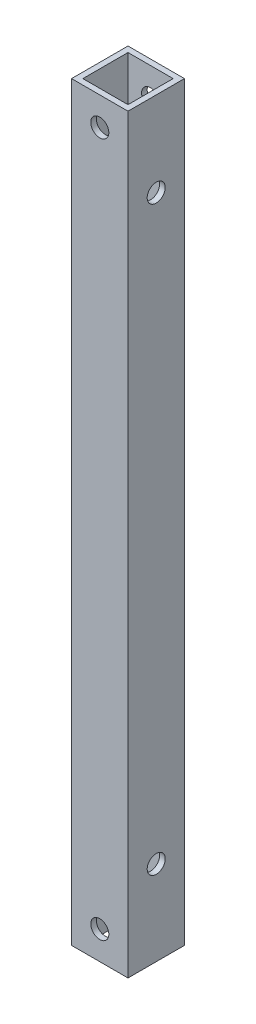
SolidWorks part; units mm, degrees
ref_plane "正面" through (0, 0, 0) normal (0, 0, 1) x (1, 0, 0)
ref_plane "平面" through (0, 0, 0) normal (0, 1, 0) x (1, 0, 0)
ref_plane "右側面" through (0, 0, 0) normal (1, 0, 0) x (0, 0, -1)
sketch "ｽｹｯﾁ1" plane through (0, 0, 0) normal (0, 0, 1) x (1, 0, 0)
  line L0 (460, 0) -> (0, 0) construction
  line L1 (17.4998, 0) -> (27.4998, 0)
  line L2 (17.4998, 0) -> (17.4998, -133)
  line L3 (17.4998, -133) -> (27.4998, -133)
  line L4 (27.4998, 0) -> (27.4998, -133)
  line L5 (459.9998, -133) -> (-0.0002, -133) construction
  line L6 (-0.0002, -133) -> (-0.0002, -123) construction
  line L7 (22.4998, 0) -> (22.4998, -133) construction
  circle A0 centre (22.4998, -5) radius 1.6
  circle A1 centre (22.4998, -128) radius 1.6
  dimension "D3" = 3.2
  dimension "D4" = 5
  dimension "D5" = 5
  dimension "D1" = 10
  dimension "D2" = 17.5
extrude "ﾎﾞｽ - 押し出し1" add sketch "ｽｹｯﾁ1" along normal blind 10
sketch "ｽｹｯﾁ2" plane through (27.4998, 0, 0) normal (1, 0, 0) x (0, 0, -1)
  line L0 (-5, 0) -> (-5, -133) construction
  line L1 (-10, 0) -> (0, 0) construction
  line L2 (-10, -133) -> (0, -133) construction
  circle A0 centre (-5, -118) radius 1.6
  circle A1 centre (-5, -15) radius 1.6
  dimension "D1" = 3.2
  dimension "D2" = 15
  dimension "D3" = 15
extrude "ｶｯﾄ - 押し出し1" cut sketch "ｽｹｯﾁ2" against normal blind 15
sketch "ｽｹｯﾁ3" plane through (0, -133, 0) normal (0, -1, 0) x (1, 0, 0)
  line L8 (18.4998, 1) -> (26.4998, 1)
  line L9 (26.4998, 1) -> (26.4998, 9)
  line L10 (26.4998, 9) -> (18.4998, 9)
  line L11 (18.4998, 9) -> (18.4998, 1)
  line L12 (18.4998, 1) -> (26.4998, 1)
  line L13 (26.4998, 1) -> (26.4998, 9)
  line L14 (26.4998, 9) -> (18.4998, 9)
  line L15 (18.4998, 9) -> (18.4998, 1)
  dimension "D1" = 1
extrude "ｶｯﾄ - 押し出し2" cut sketch "ｽｹｯﾁ3" against normal blind 1000
